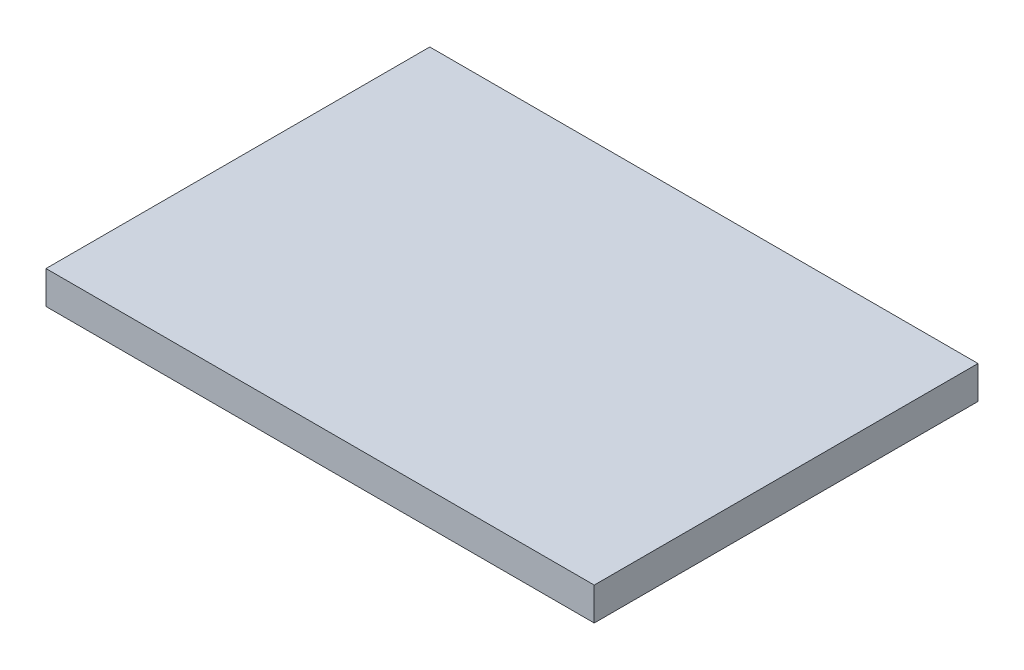
SolidWorks part; units mm, degrees
ref_plane "Front Plane" through (0, 0, 0) normal (0, 0, 1) x (1, 0, 0)
ref_plane "Top Plane" through (0, 0, 0) normal (0, 1, 0) x (1, 0, 0)
ref_plane "Right Plane" through (0, 0, 0) normal (1, 0, 0) x (0, 0, -1)
sketch "Sketch1" plane through (0, 0, 0) normal (0, 1, 0) x (1, 0, 0)
  line L1 (-25, -17.5) -> (25, -17.5)
  line L2 (-25, -17.5) -> (-25, 17.5)
  line L3 (-25, 17.5) -> (25, 17.5)
  line L4 (25, -17.5) -> (25, 17.5)
  line L5 (-25, -17.5) -> (25, 17.5) construction
  line L6 (-25, 17.5) -> (25, -17.5) construction
  point P0 (0, 0)
  dimension "D1" = 50
  dimension "D2" = 35
extrude "Boss-Extrude1" add sketch "Sketch1" along normal mid plane 3
